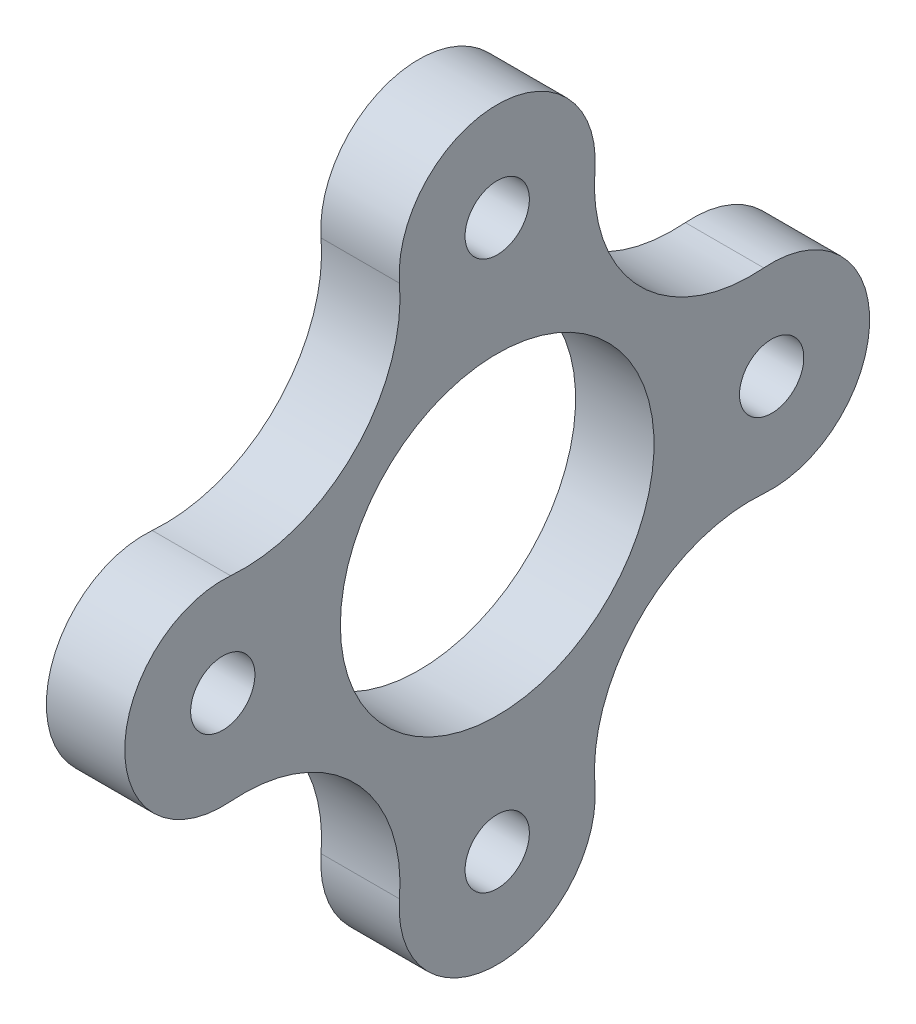
SolidWorks part; units mm, degrees
ref_plane "Front Plane" through (0, 0, 0) normal (0, 0, 1) x (1, 0, 0)
ref_plane "Top Plane" through (0, 0, 0) normal (0, 1, 0) x (1, 0, 0)
ref_plane "Right Plane" through (0, 0, 0) normal (1, 0, 0) x (0, 0, -1)
sketch "Sketch1" plane through (33.3375, 0, 0) normal (-1, 0, 0) x (0, 0, 1)
  line L0 (-3.2066, 186.9315) -> (19.0184, 186.9315) construction
  line L1 (19.0184, 186.9315) -> (26.9559, 186.9315) construction
  line L2 (-3.2066, 164.7065) -> (-3.2066, 156.769) construction
  circle A0 centre (-3.2066, 186.9315) radius 12.7 construction
  circle A1 centre (-3.2066, 186.9315) radius 12.7
  circle A2 centre (19.0184, 186.9315) radius 2.6035
  circle A3 centre (-3.2066, 164.7065) radius 2.6035
  circle A4 centre (-25.4316, 186.9315) radius 2.6035
  circle A5 centre (-3.2066, 209.1565) radius 2.6035
  arc A7 (26.9559, 186.9315) -> (18.3823, 179.0196) centre (19.0184, 186.9315) cw
  arc A8 (-3.2066, 156.769) -> (4.7054, 165.3426) centre (-3.2066, 164.7065) ccw
  arc A9 (4.7054, 165.3426) -> (18.3823, 179.0196) centre (17.3645, 166.3604) cw
  arc A10 (-33.3691, 186.9315) -> (-24.7955, 179.0196) centre (-25.4316, 186.9315) ccw
  arc A11 (-24.7955, 179.0196) -> (-11.1185, 165.3426) centre (-23.7777, 166.3604) cw
  arc A12 (-3.2066, 156.769) -> (-11.1185, 165.3426) centre (-3.2066, 164.7065) cw
  arc A13 (-3.2066, 217.094) -> (-11.1185, 208.5204) centre (-3.2066, 209.1565) ccw
  arc A14 (-11.1185, 208.5204) -> (-24.7955, 194.8435) centre (-23.7777, 207.5026) cw
  arc A15 (-33.3691, 186.9315) -> (-24.7955, 194.8435) centre (-25.4316, 186.9315) cw
  arc A16 (26.9559, 186.9315) -> (18.3823, 194.8435) centre (19.0184, 186.9315) ccw
  arc A17 (18.3823, 194.8435) -> (4.7054, 208.5204) centre (17.3645, 207.5026) cw
  arc A18 (-3.2066, 217.094) -> (4.7054, 208.5204) centre (-3.2066, 209.1565) cw
  point P14 (-3.2066, 186.9315)
  point P41 (-3.2066, 186.9315)
  dimension "D3" = 5.207
  dimension "D4" = 7.9375
  dimension "D5" = 12.7
  dimension "D1" = 22.225
  dimension "D2" = 4
  dimension "D6" = 4
extrude "Boss-Extrude1" add sketch "Sketch1" along normal blind 6.35
